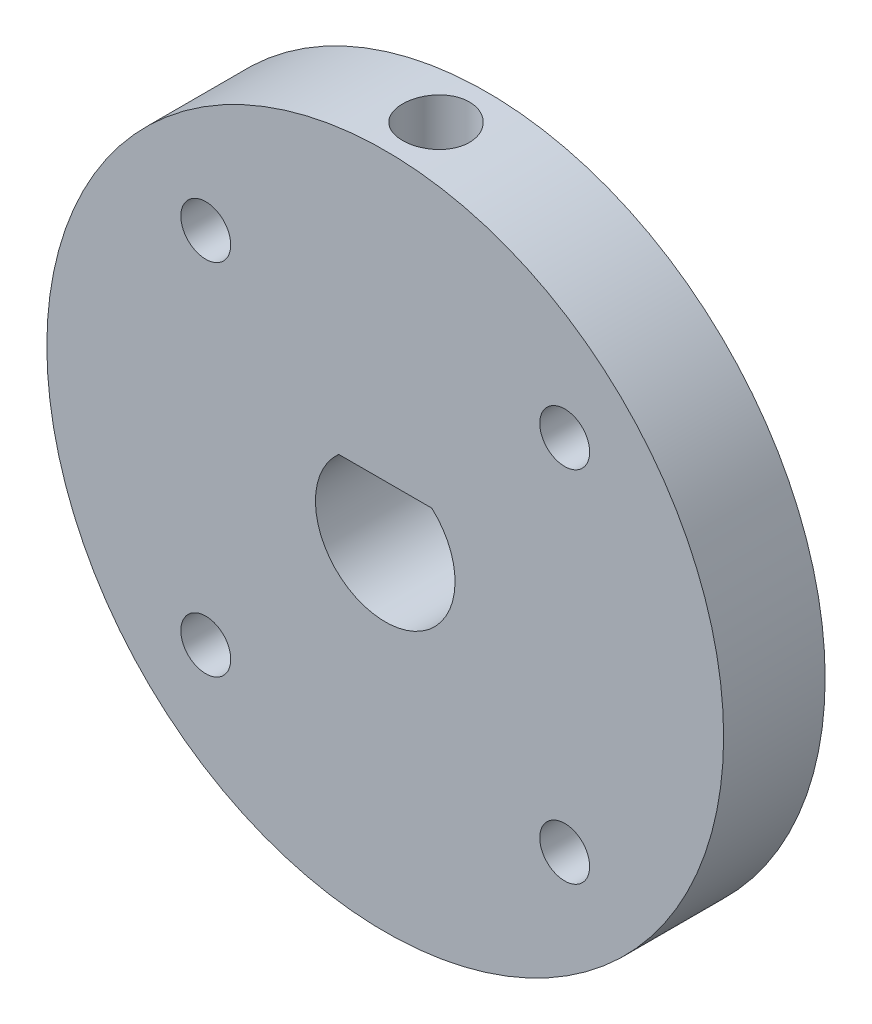
SolidWorks part; units mm, degrees
ref_plane "Front" through (0, 0, 0) normal (0, 0, 1) x (1, 0, 0)
ref_plane "Top" through (0, 0, 0) normal (0, 1, 0) x (1, 0, 0)
ref_plane "Right" through (0, 0, 0) normal (1, 0, 0) x (0, 0, -1)
sketch "Sketch1" plane through (0, 0, 0) normal (0, 0, 1) x (1, 0, 0)
  line L0 (-32.5019, 0) -> (34.1972, 0) construction
  line L1 (-2.7495, 3.075) -> (2.7495, 3.075)
  line L2 (0, 0) -> (10.6066, 10.6066) construction
  circle A0 centre (0, 0) radius 4.125
  circle A1 centre (0, 0) radius 15 construction
  circle A2 centre (0, 0) radius 20
  circle A3 centre (10.6066, 10.6066) radius 1.475
  circle A7 centre (10.6066, -10.6066) radius 1.475
  circle A8 centre (-10.6066, -10.6066) radius 1.475
  circle A9 centre (-10.6066, 10.6066) radius 1.475
  point P17 (0, 0)
  point P18 (0, -4.125)
  point P22 (0, 0)
  dimension "D1" = 8.25
  dimension "D2" = 30
  dimension "D3" = 40
  dimension "D4" = 2.95
  dimension "D5" = 45
  dimension "D6" = 7.2
  dimension "D7" = 4
extrude "Boss-Extrude1" add sketch "Sketch1" along normal blind 6
sketch "Sketch2" plane through (0, 0, 0) normal (0, 1, 0) x (1, 0, 0)
  line L0 (-8.7796, -3) -> (9.9295, -3) construction
  line L1 (-20, -6) -> (20, -6) construction
  line L2 (-2.7495, 0) -> (2.7495, 0) construction
  circle A0 centre (0, -3) radius 1.975
  dimension "D1" = 3.95
extrude "Cut-Extrude1" cut sketch "Sketch2" along normal up to next
